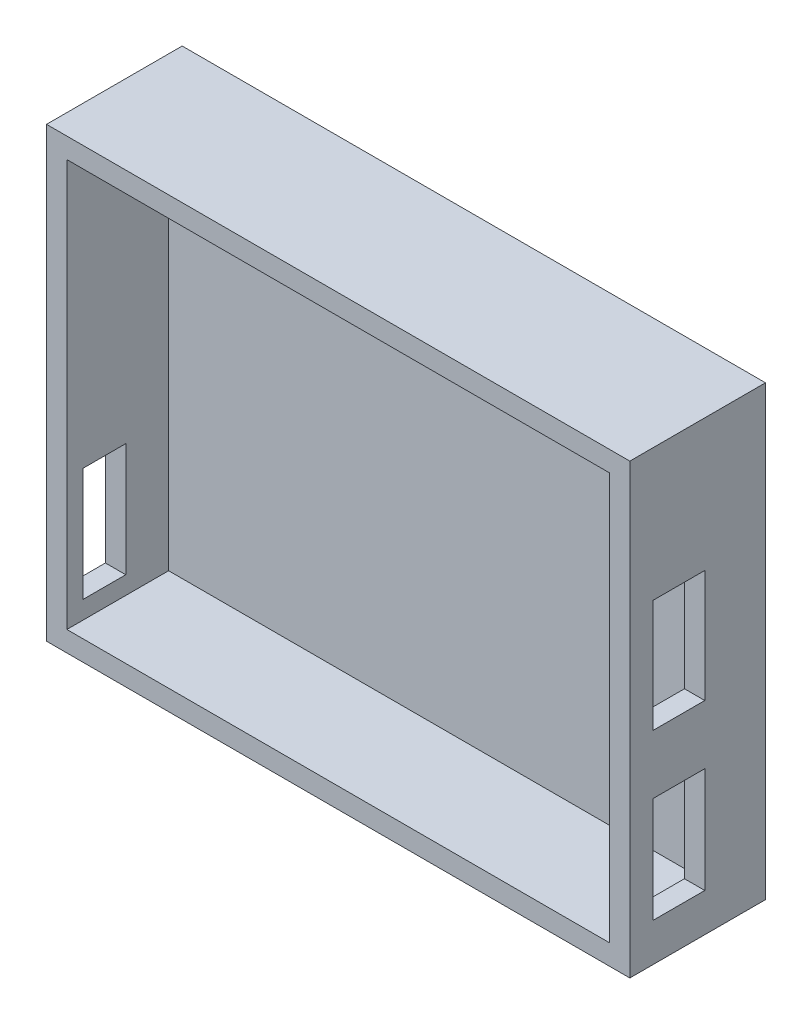
SolidWorks part; units mm, degrees
ref_plane "Plan de face" through (0, 0, 0) normal (0, 0, 1) x (1, 0, 0)
ref_plane "Plan de dessus" through (0, 0, 0) normal (0, 1, 0) x (1, 0, 0)
ref_plane "Plan de droite" through (0, 0, 0) normal (1, 0, 0) x (0, 0, -1)
sketch "Esquisse4" plane through (0, 0, 0) normal (0, 0, 1) x (1, 0, 0)
  line L1 (-35.8301, 27.3359) -> (50.1699, 27.3359)
  line L2 (-35.8301, 27.3359) -> (-35.8301, -38.6641)
  line L3 (-35.8301, -38.6641) -> (50.1699, -38.6641)
  line L4 (50.1699, 27.3359) -> (50.1699, -38.6641)
  dimension "D1" = 86
  dimension "D2" = 66
extrude "Boss.-Extru.3" add sketch "Esquisse4" along normal blind 5
sketch "Esquisse5" plane through (0, 0, 5) normal (0, 0, 1) x (1, 0, 0)
  line L1 (-35.8301, 27.3359) -> (50.1699, 27.3359)
  line L2 (-35.8301, 27.3359) -> (-35.8301, -38.6641)
  line L3 (-35.8301, -38.6641) -> (50.1699, -38.6641)
  line L4 (50.1699, 27.3359) -> (50.1699, -38.6641)
  line L5 (-32.8301, 24.3359) -> (47.1699, 24.3359)
  line L6 (-32.8301, 24.3359) -> (-32.8301, -35.6641)
  line L7 (-32.8301, -35.6641) -> (47.1699, -35.6641)
  line L8 (47.1699, 24.3359) -> (47.1699, -35.6641)
  dimension "D1" = 3
  dimension "D2" = 3
  dimension "D3" = 3
  dimension "D4" = 3
extrude "Boss.-Extru.5" add sketch "Esquisse5" along normal blind 15
sketch "Esquisse7" plane through (-35.8301, 0, 0) normal (-1, 0, 0) x (0, 0, 1)
  line L1 (11.3181, -16.2748) -> (17.645, -16.2748)
  line L2 (11.3181, -16.2748) -> (11.3181, -33.0147)
  line L3 (11.3181, -33.0147) -> (17.645, -33.0147)
  line L4 (17.645, -16.2748) -> (17.645, -33.0147)
extrude "Enlèv. mat.-Extru.3" cut sketch "Esquisse7" against normal blind 15
sketch "Esquisse8" plane through (50.1699, 0, 0) normal (1, 0, 0) x (0, 0, -1)
  line L1 (-16.5905, -17.4611) -> (-8.9455, -17.4611)
  line L2 (-16.5905, -17.4611) -> (-16.5905, -33.0147)
  line L3 (-16.5905, -33.0147) -> (-8.9455, -33.0147)
  line L4 (-8.9455, -17.4611) -> (-8.9455, -33.0147)
  line L5 (-16.5905, 7.8465) -> (-8.9455, 7.8465)
  line L6 (-16.5905, 7.8465) -> (-16.5905, -8.7616)
  line L7 (-16.5905, -8.7616) -> (-8.9455, -8.7616)
  line L8 (-8.9455, 7.8465) -> (-8.9455, -8.7616)
extrude "Enlèv. mat.-Extru.4" cut sketch "Esquisse8" against normal blind 15
